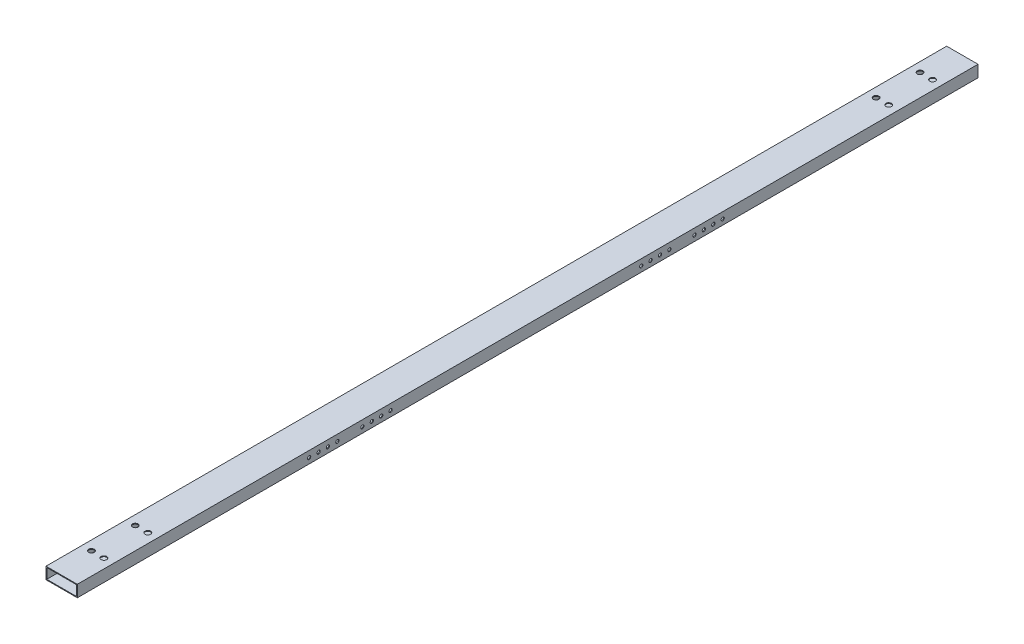
SolidWorks part; units mm, degrees
material "1100-H12 棒材(SS)"
ref_plane "前视基准面" through (0, 0, 0) normal (0, 0, 1) x (1, 0, 0)
ref_plane "上视基准面" through (0, 0, 0) normal (0, 1, 0) x (1, 0, 0)
ref_plane "右视基准面" through (0, 0, 0) normal (1, 0, 0) x (0, 0, -1)
other "Configuration Table"
sketch "草图1" plane through (0, 0, 0) normal (0, 0, 1) x (1, 0, 0)
  line L1 (0, 0) -> (40, 0)
  line L2 (0, 0) -> (0, 15)
  line L3 (0, 15) -> (40, 15)
  line L4 (40, 0) -> (40, 15)
  line L5 (1, 1) -> (39, 1)
  line L6 (1, 1) -> (1, 14)
  line L7 (1, 14) -> (39, 14)
  line L8 (39, 1) -> (39, 14)
  dimension "D1" = 40
  dimension "D2" = 15
  dimension "D3" = 1
  dimension "D4" = 1
  dimension "D5" = 1
  dimension "D6" = 1
extrude "凸台-拉伸1" add sketch "草图1" along normal blind 1150
sketch "草图2" plane through (0, 0, 0) normal (0, -1, 0) x (1, 0, 0)
  line L12 (35, 55) -> (33, 55)
  line L13 (35, 40) -> (35, 55)
  line L14 (5, 40) -> (35, 40)
  line L15 (5, 55) -> (5, 40)
  line L16 (7, 55) -> (5, 55)
  line L17 (7, 93) -> (7, 55)
  line L18 (5, 93) -> (7, 93)
  line L19 (5, 108) -> (5, 93)
  line L20 (35, 108) -> (5, 108)
  line L21 (35, 93) -> (35, 108)
  line L22 (33, 93) -> (35, 93)
  line L23 (33, 55) -> (33, 93)
  line L24 (35, 55) -> (33, 55) construction
  line L25 (35, 40) -> (35, 55) construction
  line L26 (5, 40) -> (35, 40) construction
  line L27 (5, 55) -> (5, 40) construction
  line L28 (7, 55) -> (5, 55) construction
  line L29 (7, 93) -> (7, 55) construction
  line L30 (5, 93) -> (7, 93) construction
  line L31 (5, 108) -> (5, 93) construction
  line L32 (35, 108) -> (5, 108) construction
  line L33 (35, 93) -> (35, 108) construction
  line L34 (33, 93) -> (35, 93) construction
  line L35 (33, 55) -> (33, 93) construction
  circle A0 centre (12, 102) radius 3.5 construction
  circle A1 centre (28, 102) radius 3.5 construction
  circle A2 centre (12, 46) radius 3.5 construction
  circle A3 centre (28, 46) radius 3.5 construction
  circle A4 centre (12, 102) radius 3.5 construction
  circle A5 centre (28, 102) radius 3.5 construction
  circle A6 centre (12, 46) radius 3.5 construction
  circle A7 centre (28, 46) radius 3.5 construction
  circle A8 centre (12, 46) radius 3.575
  circle A9 centre (12, 1048) radius 3.5
  circle A10 centre (12, 1048) radius 3.5 construction
  circle A11 centre (28, 1048) radius 3.5
  circle A12 centre (28, 1048) radius 3.5 construction
  circle A13 centre (12, 1104) radius 3.5
  circle A14 centre (12, 1104) radius 3.5 construction
  circle A15 centre (28, 1104) radius 3.5
  circle A16 centre (28, 1104) radius 3.5 construction
  circle A17 centre (28, 46) radius 3.575
  circle A18 centre (12, 102) radius 3.575
  circle A19 centre (28, 102) radius 3.575
  circle A20 centre (12, 1104) radius 3.575
  circle A21 centre (28, 1104) radius 3.575
  circle A22 centre (12, 1048) radius 3.575
  circle A23 centre (28, 1048) radius 3.575
  dimension "D6" = 7.15
  dimension "D1" = 0
  dimension "D2" = 0
  dimension "D3" = 0
  dimension "D4" = 0
  dimension "D5" = 0
extrude "切除-拉伸1" cut sketch "草图2" against normal through all
sketch "草图3" plane through (40, 0, 0) normal (1, 0, 0) x (0, 0, -1)
  circle A1 centre (-366, -6) radius 2.1
  circle A2 centre (-366, -6) radius 2.1 construction
  circle A3 centre (-390, -22) radius 2.1
  circle A4 centre (-390, -22) radius 2.1 construction
  circle A5 centre (-366, -22) radius 2.1
  circle A6 centre (-366, -22) radius 2.1 construction
  circle A7 centre (-430, 7) radius 2.1
  circle A8 centre (-430, 7) radius 2.1
  circle A9 centre (-418, 7) radius 2.1
  circle A10 centre (-418, 7) radius 2.1
  circle A11 centre (-338, 7) radius 2.1
  circle A12 centre (-338, 7) radius 2.1
  circle A13 centre (-326, 7) radius 2.1
  circle A14 centre (-326, 7) radius 2.1
  circle A15 centre (-390, -6) radius 2.1
  circle A16 centre (-390, -6) radius 2.1 construction
  circle A17 centre (-406, 7) radius 2.1
  circle A18 centre (-406, 7) radius 2.1
  circle A19 centre (-394, 7) radius 2.1
  circle A20 centre (-394, 7) radius 2.1
  circle A21 centre (-362, 7) radius 2.1
  circle A22 centre (-362, 7) radius 2.1
  circle A23 centre (-350, 7) radius 2.1
  circle A24 centre (-350, 7) radius 2.1
  circle A25 centre (-790, -6) radius 2.1
  circle A26 centre (-790, -6) radius 2.1 construction
  circle A27 centre (-814, -22) radius 2.1
  circle A28 centre (-814, -22) radius 2.1 construction
  circle A29 centre (-790, -22) radius 2.1
  circle A30 centre (-790, -22) radius 2.1 construction
  circle A31 centre (-854, 7) radius 2.1
  circle A32 centre (-854, 7) radius 2.1
  circle A33 centre (-842, 7) radius 2.1
  circle A34 centre (-842, 7) radius 2.1
  circle A35 centre (-762, 7) radius 2.1
  circle A36 centre (-762, 7) radius 2.1
  circle A37 centre (-750, 7) radius 2.1
  circle A38 centre (-750, 7) radius 2.1
  circle A39 centre (-814, -6) radius 2.1
  circle A40 centre (-814, -6) radius 2.1 construction
  circle A41 centre (-830, 7) radius 2.1
  circle A42 centre (-830, 7) radius 2.1
  circle A43 centre (-818, 7) radius 2.1
  circle A44 centre (-818, 7) radius 2.1
  circle A45 centre (-786, 7) radius 2.1
  circle A46 centre (-786, 7) radius 2.1
  circle A47 centre (-774, 7) radius 2.1
  circle A48 centre (-774, 7) radius 2.1
  dimension "D1" = 0
  dimension "D2" = 0
  dimension "D3" = 0
  dimension "D4" = 0
  dimension "D5" = 0
  dimension "D6" = 0
  dimension "D7" = 0
  dimension "D8" = 0
  dimension "D9" = 0
  dimension "D10" = 0
  dimension "D11" = 0
  dimension "D12" = 0
  dimension "D13" = 0
  dimension "D14" = 0
  dimension "D15" = 0
  dimension "D16" = 0
  dimension "D17" = 0
  dimension "D18" = 0
  dimension "D19" = 0
  dimension "D20" = 0
  dimension "D21" = 0
  dimension "D22" = 0
  dimension "D23" = 0
  dimension "D24" = 0
extrude "切除-拉伸2" cut sketch "草图3" against normal through all
